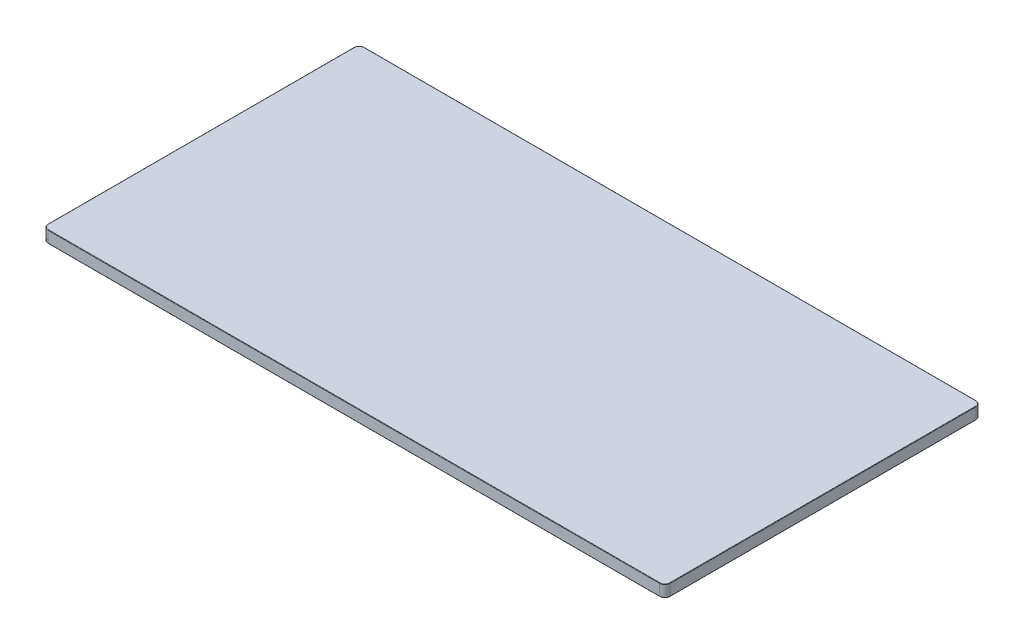
SolidWorks part; units mm, degrees
ref_plane "Front Plane" through (0, 0, 0) normal (0, 0, 1) x (1, 0, 0)
ref_plane "Top Plane" through (0, 0, 0) normal (0, 1, 0) x (1, 0, 0)
ref_plane "Right Plane" through (0, 0, 0) normal (1, 0, 0) x (0, 0, -1)
sketch "Sketch1" plane through (411.6454, 18029.9073, 0.2815) normal (0, 1, 0) x (1, 0, 0)
  line L1 (-1160.9454, -380.7185) -> (337.6546, -380.7185)
  line L2 (-1160.9454, -380.7185) -> (-1160.9454, 381.2815)
  line L3 (-1160.9454, 381.2815) -> (337.6546, 381.2815)
  line L4 (337.6546, -380.7185) -> (337.6546, 381.2815)
  line L5 (-1160.9454, -380.7185) -> (337.6546, 381.2815) construction
  line L6 (-1160.9454, 381.2815) -> (337.6546, -380.7185) construction
  point P0 (-411.6454, 0.2815)
  dimension "D1" = 1498.6
  dimension "D2" = 762
extrude "Boss-Extrude1" add sketch "Sketch1" along normal blind 28.575
fillet "Fillet1" radius 12.7 4 edges at (-749.3, 18044.1948, 381) (749.3, 18044.1948, -381) (749.3, 18044.1948, 381) (-749.3, 18044.1948, -381)
fillet "Fillet2" radius 1 16 edges at (-745.5803, 18029.9073, -377.2803) (0, 18029.9073, -381) (745.5803, 18029.9073, -377.2803) (749.3, 18029.9073, 0) (745.5803, 18029.9073, 377.2803) (0, 18029.9073, 381) (-745.5803, 18029.9073, 377.2803) (-745.5803, 18058.4823, -377.2803) (0, 18058.4823, -381) (745.5803, 18058.4823, -377.2803) (749.3, 18058.4823, 0) (745.5803, 18058.4823, 377.2803) (0, 18058.4823, 381) (-745.5803, 18058.4823, 377.2803) (-749.3, 18029.9073, 0) (-749.3, 18058.4823, 0)
